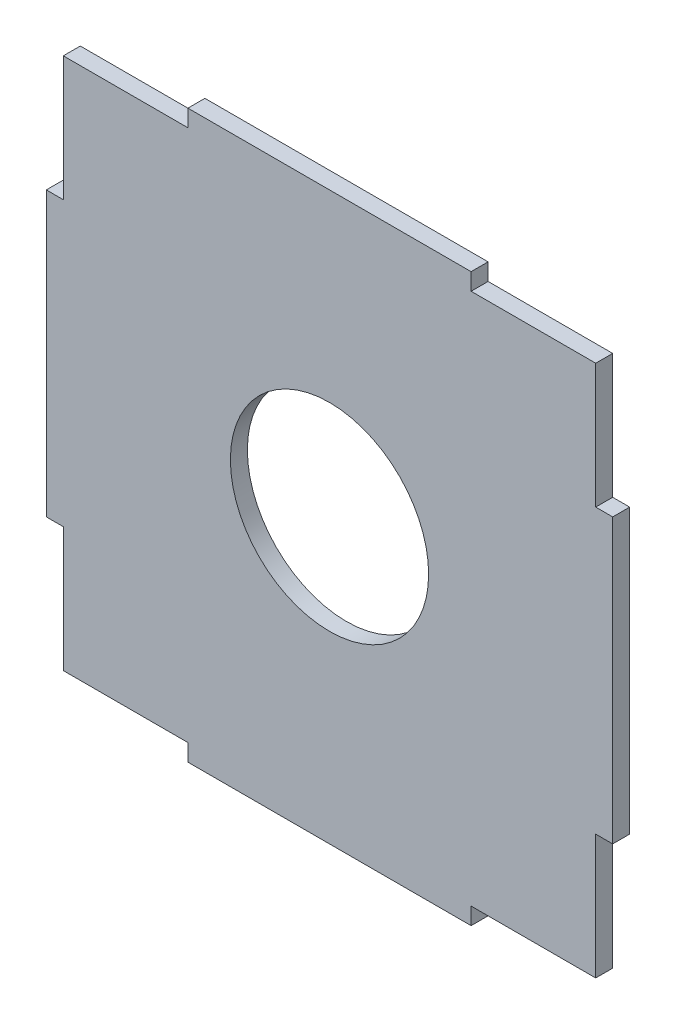
SolidWorks part; units mm, degrees
ref_plane "前视基准面" through (0, 0, 0) normal (0, 0, 1) x (1, 0, 0)
ref_plane "上视基准面" through (0, 0, 0) normal (0, 1, 0) x (1, 0, 0)
ref_plane "右视基准面" through (0, 0, 0) normal (1, 0, 0) x (0, 0, -1)
sketch "草图1" plane through (0, 0, 0) normal (0, 0, 1) x (1, 0, 0)
  line L0 (-75, 100) -> (-75, 97)
  line L1 (-25, 0) -> (-75, 0)
  line L2 (0, 25) -> (0, 75)
  line L3 (-25, 100) -> (-75, 100)
  line L4 (-100, 25) -> (-100, 75)
  line L5 (-97, 97) -> (-75, 97)
  line L6 (-97, 97) -> (-97, 75)
  line L7 (-97, 3) -> (-75, 3)
  line L8 (-3, 97) -> (-3, 75)
  line L9 (-25, 100) -> (-25, 97)
  line L10 (-100, 75) -> (-97, 75)
  line L11 (-100, 25) -> (-97, 25)
  line L12 (-25, 97) -> (-3, 97)
  line L13 (-75, 3) -> (-75, 0)
  line L14 (-3, 75) -> (0, 75)
  line L15 (-25, 3) -> (-25, 0)
  line L16 (-3, 25) -> (-3, 3)
  line L17 (-3, 25) -> (0, 25)
  line L18 (-25, 3) -> (-3, 3)
  line L19 (-97, 25) -> (-97, 3)
  dimension "D3" = 3
  dimension "D4" = 3
  dimension "D5" = 3
  dimension "D6" = 3
  dimension "D7" = 25
  dimension "D8" = 25
  dimension "D9" = 25
  dimension "D10" = 25
extrude "凸台-拉伸1" add sketch "草图1" along normal blind 3
sketch "草图2" plane through (0, 0, 0) normal (0, 0, -1) x (-1, 0, 0)
  line L0 (25, 100) -> (75, 100) construction
  line L1 (100, 75) -> (100, 25) construction
  circle A0 centre (50, 50) radius 17.5
  dimension "D1" = 35
  dimension "D2" = 50
  dimension "D3" = 50
extrude "切除-拉伸1" cut sketch "草图2" against normal through all
